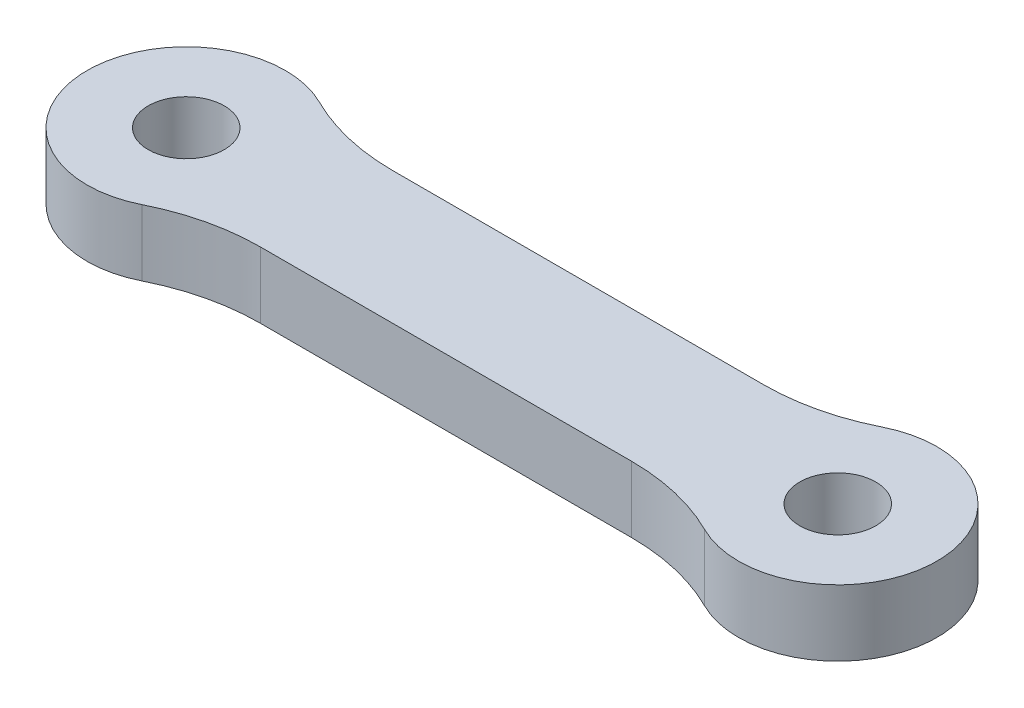
SolidWorks part; units mm, degrees
ref_plane "Спереди" through (0, 0, 0) normal (0, 0, 1) x (1, 0, 0)
ref_plane "Сверху" through (0, 0, 0) normal (0, 1, 0) x (1, 0, 0)
ref_plane "Справа" through (0, 0, 0) normal (1, 0, 0) x (0, 0, -1)
sketch "Эскиз1" plane through (0, 0, 0) normal (0, 1, 0) x (1, 0, 0)
  line L0 (0, 0) -> (19.7, 0) construction
  line L1 (2.2361, 2) -> (17.4639, 2)
  line L3 (17.4639, -2) -> (2.2361, -2)
  circle A0 centre (0, 0) radius 1.15
  arc A1 (2.2361, 2) -> (2.2361, -2) centre (0, 0) ccw
  circle A2 centre (19.7, 0) radius 1.15
  arc A3 (17.4639, -2) -> (17.4639, 2) centre (19.7, 0) ccw
  dimension "D4" = 2.3
  dimension "D5" = 2.3
  dimension "D6" = 6
  dimension "D7" = 6
  dimension "D1" = 19.7
  dimension "D2" = 2
  dimension "D3" = 2
extrude "Бобышка-Вытянуть1" add sketch "Эскиз1" along normal blind 2
fillet "Скругление1" radius 6.5 4 edges at (17.4639, 1, -2) (17.4639, 1, 2) (2.2361, 1, 2) (2.2361, 1, -2)
